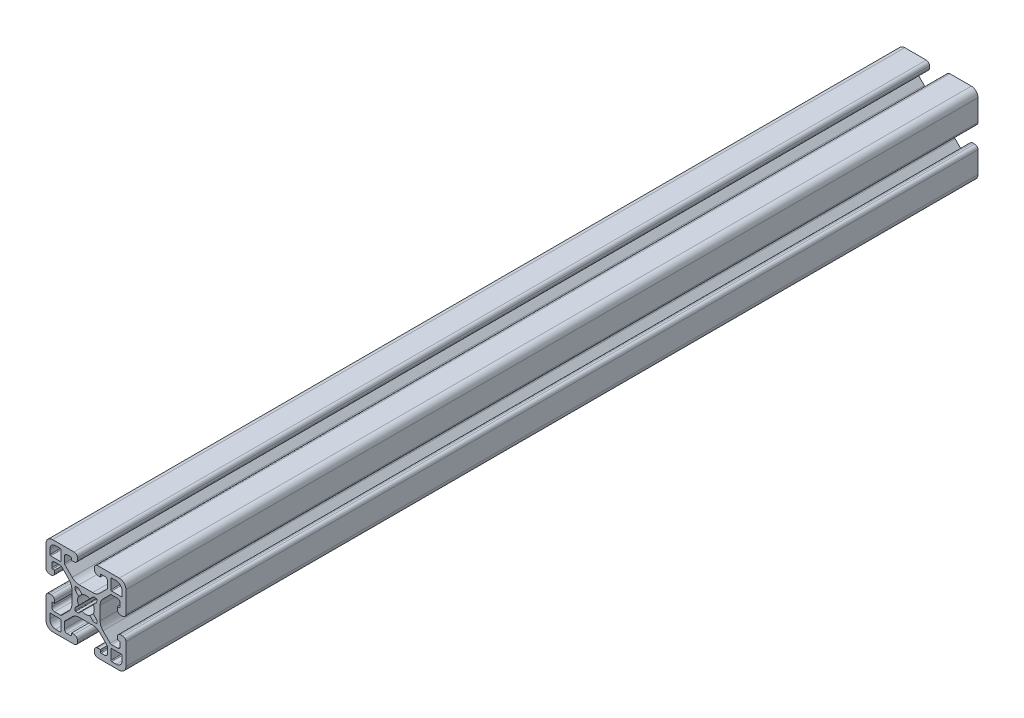
SolidWorks part; units mm, degrees
material "6105-T5 Aluminum"
ref_plane "Front Plane" through (0, 0, 0) normal (0, 0, 1) x (1, 0, 0)
ref_plane "Top Plane" through (0, 0, 0) normal (0, 1, 0) x (1, 0, 0)
ref_plane "Right Plane" through (0, 0, 0) normal (1, 0, 0) x (0, 0, -1)
sketch "Sketch1" plane through (0, 0, 0) normal (0, 0, 1) x (1, 0, 0)
  line L0 (-12.2428, -17.2466) -> (-14.4526, -17.2466)
  line L1 (-17.2466, -14.4526) -> (-17.2466, -12.2428)
  line L2 (-16.8656, -11.8618) -> (-12.2428, -11.8618)
  line L3 (-11.8618, -12.2428) -> (-11.8618, -16.8656)
  line L4 (12.2428, 17.2466) -> (14.4526, 17.2466)
  line L5 (17.2466, 14.4526) -> (17.2466, 12.2428)
  line L6 (16.8656, 11.8618) -> (12.2428, 11.8618)
  line L7 (11.8618, 12.2428) -> (11.8618, 16.8656)
  line L8 (1.5823, 3.1988) -> (3.3048, 4.9212)
  line L9 (3.9334, 5.1816) -> (4.9276, 5.1816)
  line L10 (5.1816, 4.9276) -> (5.1816, 3.9334)
  line L11 (4.9212, 3.3048) -> (3.1988, 1.5823)
  line L12 (3.1988, -1.5823) -> (4.9212, -3.3048)
  line L13 (5.1816, -3.9334) -> (5.1816, -4.9276)
  line L14 (4.9276, -5.1816) -> (3.9334, -5.1816)
  line L15 (3.3048, -4.9212) -> (1.5823, -3.1988)
  line L16 (-1.5823, -3.1988) -> (-3.3048, -4.9212)
  line L17 (-3.9334, -5.1816) -> (-4.9276, -5.1816)
  line L18 (-5.1816, -4.9276) -> (-5.1816, -3.9334)
  line L19 (-4.9212, -3.3048) -> (-3.1988, -1.5823)
  line L20 (-3.1988, 1.5823) -> (-4.9212, 3.3048)
  line L21 (-5.1816, 3.9334) -> (-5.1816, 4.9276)
  line L22 (-4.9276, 5.1816) -> (-3.9334, 5.1816)
  line L23 (-3.3048, 4.9212) -> (-1.5823, 3.1988)
  line L24 (-17.2466, 12.2428) -> (-17.2466, 14.4526)
  line L25 (-14.4526, 17.2466) -> (-12.2428, 17.2466)
  line L26 (-11.8618, 16.8656) -> (-11.8618, 12.2428)
  line L27 (-12.2428, 11.8618) -> (-16.8656, 11.8618)
  line L28 (17.2466, -12.2428) -> (17.2466, -14.4526)
  line L29 (14.4526, -17.2466) -> (12.2428, -17.2466)
  line L30 (11.8618, -16.8656) -> (11.8618, -12.2428)
  line L31 (12.2428, -11.8618) -> (16.8656, -11.8618)
  line L32 (-16.2859, 7.239) -> (-16.2859, 9.017)
  line L33 (-15.0159, 10.287) -> (-12.2178, 10.287)
  line L34 (-11.5892, 10.0266) -> (-8.1292, 6.5666)
  line L35 (-6.738, 3.208) -> (-6.738, -3.208)
  line L36 (-8.1292, -6.5666) -> (-11.5892, -10.0266)
  line L37 (-12.2178, -10.287) -> (-15.0159, -10.287)
  line L38 (-16.2859, -9.017) -> (-16.2859, -7.239)
  line L39 (-15.9049, -6.858) -> (-14.986, -6.858)
  line L40 (-14.986, -6.858) -> (-14.986, -5.6388)
  line L41 (-16.5608, -4.064) -> (-17.4752, -4.064)
  line L42 (-19.05, -5.6388) -> (-19.05, -15.875)
  line L43 (-15.875, -19.05) -> (-5.6388, -19.05)
  line L44 (-4.064, -17.4752) -> (-4.064, -16.5608)
  line L45 (-5.6388, -14.986) -> (-6.858, -14.986)
  line L46 (-6.858, -14.986) -> (-6.858, -15.9049)
  line L47 (-7.239, -16.2859) -> (-9.017, -16.2859)
  line L48 (-10.287, -15.0159) -> (-10.287, -12.2178)
  line L49 (-10.0266, -11.5892) -> (-6.5666, -8.1292)
  line L50 (-3.208, -6.738) -> (3.208, -6.738)
  line L51 (6.5666, -8.1292) -> (10.0266, -11.5892)
  line L52 (10.287, -12.2178) -> (10.287, -15.0159)
  line L53 (9.017, -16.2859) -> (7.239, -16.2859)
  line L54 (6.858, -15.9049) -> (6.858, -14.986)
  line L55 (6.858, -14.986) -> (5.6388, -14.986)
  line L56 (4.064, -16.5608) -> (4.064, -17.4752)
  line L57 (5.6388, -19.05) -> (15.875, -19.05)
  line L58 (19.05, -15.875) -> (19.05, -5.6388)
  line L59 (17.4752, -4.064) -> (16.5608, -4.064)
  line L60 (14.986, -5.6388) -> (14.986, -6.858)
  line L61 (14.986, -6.858) -> (15.9049, -6.858)
  line L62 (16.2859, -7.239) -> (16.2859, -9.017)
  line L63 (15.0159, -10.287) -> (12.2178, -10.287)
  line L64 (11.5892, -10.0266) -> (8.1292, -6.5666)
  line L65 (6.738, -3.208) -> (6.738, 3.208)
  line L66 (8.1292, 6.5666) -> (11.5892, 10.0266)
  line L67 (12.2178, 10.287) -> (15.0159, 10.287)
  line L68 (16.2859, 9.017) -> (16.2859, 7.239)
  line L69 (15.9049, 6.858) -> (14.986, 6.858)
  line L70 (14.986, 6.858) -> (14.986, 5.6388)
  line L71 (16.5608, 4.064) -> (17.4752, 4.064)
  line L72 (19.05, 5.6388) -> (19.05, 15.875)
  line L73 (15.875, 19.05) -> (5.6388, 19.05)
  line L74 (4.064, 17.4752) -> (4.064, 16.5608)
  line L75 (5.6388, 14.986) -> (6.858, 14.986)
  line L76 (6.858, 14.986) -> (6.858, 15.9049)
  line L77 (7.239, 16.2859) -> (9.017, 16.2859)
  line L78 (10.287, 15.0159) -> (10.287, 12.2178)
  line L79 (10.0266, 11.5892) -> (6.5666, 8.1292)
  line L80 (3.208, 6.738) -> (-3.208, 6.738)
  line L81 (-6.5666, 8.1292) -> (-10.0266, 11.5892)
  line L82 (-10.287, 12.2178) -> (-10.287, 15.0159)
  line L83 (-9.017, 16.2859) -> (-7.239, 16.2859)
  line L84 (-6.858, 15.9049) -> (-6.858, 14.986)
  line L85 (-6.858, 14.986) -> (-5.6388, 14.986)
  line L86 (-4.064, 16.5608) -> (-4.064, 17.4752)
  line L87 (-5.6388, 19.05) -> (-15.875, 19.05)
  line L88 (-19.05, 15.875) -> (-19.05, 5.6388)
  line L89 (-17.4752, 4.064) -> (-16.5608, 4.064)
  line L90 (-14.986, 5.6388) -> (-14.986, 6.858)
  line L91 (-14.986, 6.858) -> (-15.9049, 6.858)
  arc A0 (-17.2466, -14.4526) -> (-14.4526, -17.2466) centre (-14.4526, -14.4526) ccw
  arc A1 (-16.8656, -11.8618) -> (-17.2466, -12.2428) centre (-16.8656, -12.2428) ccw
  arc A2 (-11.8618, -12.2428) -> (-12.2428, -11.8618) centre (-12.2428, -12.2428) ccw
  arc A3 (-12.2428, -17.2466) -> (-11.8618, -16.8656) centre (-12.2428, -16.8656) ccw
  arc A4 (17.2466, 14.4526) -> (14.4526, 17.2466) centre (14.4526, 14.4526) ccw
  arc A5 (16.8656, 11.8618) -> (17.2466, 12.2428) centre (16.8656, 12.2428) ccw
  arc A6 (11.8618, 12.2428) -> (12.2428, 11.8618) centre (12.2428, 12.2428) ccw
  arc A7 (12.2428, 17.2466) -> (11.8618, 16.8656) centre (12.2428, 16.8656) ccw
  arc A8 (1.178, 3.1119) -> (-1.178, 3.1119) centre (0, 0) ccw
  arc A9 (1.178, 3.1119) -> (1.5823, 3.1988) centre (1.3129, 3.4682) ccw
  arc A10 (3.9334, 5.1816) -> (3.3048, 4.9212) centre (3.9334, 4.2926) ccw
  arc A11 (5.1816, 4.9276) -> (4.9276, 5.1816) centre (4.9276, 4.9276) ccw
  arc A12 (4.9212, 3.3048) -> (5.1816, 3.9334) centre (4.2926, 3.9334) ccw
  arc A13 (3.1988, 1.5823) -> (3.1119, 1.178) centre (3.4682, 1.3129) ccw
  arc A14 (3.1119, -1.178) -> (3.1119, 1.178) centre (0, 0) ccw
  arc A15 (3.1119, -1.178) -> (3.1988, -1.5823) centre (3.4682, -1.3129) ccw
  arc A16 (5.1816, -3.9334) -> (4.9212, -3.3048) centre (4.2926, -3.9334) ccw
  arc A17 (4.9276, -5.1816) -> (5.1816, -4.9276) centre (4.9276, -4.9276) ccw
  arc A18 (3.3048, -4.9212) -> (3.9334, -5.1816) centre (3.9334, -4.2926) ccw
  arc A19 (1.5823, -3.1988) -> (1.178, -3.1119) centre (1.3129, -3.4682) ccw
  arc A20 (-1.178, -3.1119) -> (1.178, -3.1119) centre (0, 0) ccw
  arc A21 (-1.178, -3.1119) -> (-1.5823, -3.1988) centre (-1.3129, -3.4682) ccw
  arc A22 (-3.9334, -5.1816) -> (-3.3048, -4.9212) centre (-3.9334, -4.2926) ccw
  arc A23 (-5.1816, -4.9276) -> (-4.9276, -5.1816) centre (-4.9276, -4.9276) ccw
  arc A24 (-4.9212, -3.3048) -> (-5.1816, -3.9334) centre (-4.2926, -3.9334) ccw
  arc A25 (-3.1988, -1.5823) -> (-3.1119, -1.178) centre (-3.4682, -1.3129) ccw
  arc A26 (-3.1119, 1.178) -> (-3.1119, -1.178) centre (0, 0) ccw
  arc A27 (-3.1119, 1.178) -> (-3.1988, 1.5823) centre (-3.4682, 1.3129) ccw
  arc A28 (-5.1816, 3.9334) -> (-4.9212, 3.3048) centre (-4.2926, 3.9334) ccw
  arc A29 (-4.9276, 5.1816) -> (-5.1816, 4.9276) centre (-4.9276, 4.9276) ccw
  arc A30 (-3.3048, 4.9212) -> (-3.9334, 5.1816) centre (-3.9334, 4.2926) ccw
  arc A31 (-1.5823, 3.1988) -> (-1.178, 3.1119) centre (-1.3129, 3.4682) ccw
  arc A32 (-14.4526, 17.2466) -> (-17.2466, 14.4526) centre (-14.4526, 14.4526) ccw
  arc A33 (-11.8618, 16.8656) -> (-12.2428, 17.2466) centre (-12.2428, 16.8656) ccw
  arc A34 (-12.2428, 11.8618) -> (-11.8618, 12.2428) centre (-12.2428, 12.2428) ccw
  arc A35 (-17.2466, 12.2428) -> (-16.8656, 11.8618) centre (-16.8656, 12.2428) ccw
  arc A36 (14.4526, -17.2466) -> (17.2466, -14.4526) centre (14.4526, -14.4526) ccw
  arc A37 (11.8618, -16.8656) -> (12.2428, -17.2466) centre (12.2428, -16.8656) ccw
  arc A38 (12.2428, -11.8618) -> (11.8618, -12.2428) centre (12.2428, -12.2428) ccw
  arc A39 (17.2466, -12.2428) -> (16.8656, -11.8618) centre (16.8656, -12.2428) ccw
  arc A40 (-16.2859, 7.239) -> (-15.9049, 6.858) centre (-15.9049, 7.239) ccw
  arc A41 (-15.0159, 10.287) -> (-16.2859, 9.017) centre (-15.0159, 9.017) ccw
  arc A42 (-11.5892, 10.0266) -> (-12.2178, 10.287) centre (-12.2178, 9.398) ccw
  arc A43 (-6.738, 3.208) -> (-8.1292, 6.5666) centre (-11.4878, 3.208) ccw
  arc A44 (-8.1292, -6.5666) -> (-6.738, -3.208) centre (-11.4878, -3.208) ccw
  arc A45 (-12.2178, -10.287) -> (-11.5892, -10.0266) centre (-12.2178, -9.398) ccw
  arc A46 (-16.2859, -9.017) -> (-15.0159, -10.287) centre (-15.0159, -9.017) ccw
  arc A47 (-15.9049, -6.858) -> (-16.2859, -7.239) centre (-15.9049, -7.239) ccw
  arc A48 (-14.986, -5.6388) -> (-16.5608, -4.064) centre (-16.5608, -5.6388) ccw
  arc A49 (-17.4752, -4.064) -> (-19.05, -5.6388) centre (-17.4752, -5.6388) ccw
  arc A50 (-19.05, -15.875) -> (-15.875, -19.05) centre (-15.875, -15.875) ccw
  arc A51 (-5.6388, -19.05) -> (-4.064, -17.4752) centre (-5.6388, -17.4752) ccw
  arc A52 (-4.064, -16.5608) -> (-5.6388, -14.986) centre (-5.6388, -16.5608) ccw
  arc A53 (-7.239, -16.2859) -> (-6.858, -15.9049) centre (-7.239, -15.9049) ccw
  arc A54 (-10.287, -15.0159) -> (-9.017, -16.2859) centre (-9.017, -15.0159) ccw
  arc A55 (-10.0266, -11.5892) -> (-10.287, -12.2178) centre (-9.398, -12.2178) ccw
  arc A56 (-3.208, -6.738) -> (-6.5666, -8.1292) centre (-3.208, -11.4878) ccw
  arc A57 (6.5666, -8.1292) -> (3.208, -6.738) centre (3.208, -11.4878) ccw
  arc A58 (10.287, -12.2178) -> (10.0266, -11.5892) centre (9.398, -12.2178) ccw
  arc A59 (9.017, -16.2859) -> (10.287, -15.0159) centre (9.017, -15.0159) ccw
  arc A60 (6.858, -15.9049) -> (7.239, -16.2859) centre (7.239, -15.9049) ccw
  arc A61 (5.6388, -14.986) -> (4.064, -16.5608) centre (5.6388, -16.5608) ccw
  arc A62 (4.064, -17.4752) -> (5.6388, -19.05) centre (5.6388, -17.4752) ccw
  arc A63 (15.875, -19.05) -> (19.05, -15.875) centre (15.875, -15.875) ccw
  arc A64 (19.05, -5.6388) -> (17.4752, -4.064) centre (17.4752, -5.6388) ccw
  arc A65 (16.5608, -4.064) -> (14.986, -5.6388) centre (16.5608, -5.6388) ccw
  arc A66 (16.2859, -7.239) -> (15.9049, -6.858) centre (15.9049, -7.239) ccw
  arc A67 (15.0159, -10.287) -> (16.2859, -9.017) centre (15.0159, -9.017) ccw
  arc A68 (11.5892, -10.0266) -> (12.2178, -10.287) centre (12.2178, -9.398) ccw
  arc A69 (6.738, -3.208) -> (8.1292, -6.5666) centre (11.4878, -3.208) ccw
  arc A70 (8.1292, 6.5666) -> (6.738, 3.208) centre (11.4878, 3.208) ccw
  arc A71 (12.2178, 10.287) -> (11.5892, 10.0266) centre (12.2178, 9.398) ccw
  arc A72 (16.2859, 9.017) -> (15.0159, 10.287) centre (15.0159, 9.017) ccw
  arc A73 (15.9049, 6.858) -> (16.2859, 7.239) centre (15.9049, 7.239) ccw
  arc A74 (14.986, 5.6388) -> (16.5608, 4.064) centre (16.5608, 5.6388) ccw
  arc A75 (17.4752, 4.064) -> (19.05, 5.6388) centre (17.4752, 5.6388) ccw
  arc A76 (19.05, 15.875) -> (15.875, 19.05) centre (15.875, 15.875) ccw
  arc A77 (5.6388, 19.05) -> (4.064, 17.4752) centre (5.6388, 17.4752) ccw
  arc A78 (4.064, 16.5608) -> (5.6388, 14.986) centre (5.6388, 16.5608) ccw
  arc A79 (7.239, 16.2859) -> (6.858, 15.9049) centre (7.239, 15.9049) ccw
  arc A80 (10.287, 15.0159) -> (9.017, 16.2859) centre (9.017, 15.0159) ccw
  arc A81 (10.0266, 11.5892) -> (10.287, 12.2178) centre (9.398, 12.2178) ccw
  arc A82 (3.208, 6.738) -> (6.5666, 8.1292) centre (3.208, 11.4878) ccw
  arc A83 (-6.5666, 8.1292) -> (-3.208, 6.738) centre (-3.208, 11.4878) ccw
  arc A84 (-10.287, 12.2178) -> (-10.0266, 11.5892) centre (-9.398, 12.2178) ccw
  arc A85 (-9.017, 16.2859) -> (-10.287, 15.0159) centre (-9.017, 15.0159) ccw
  arc A86 (-6.858, 15.9049) -> (-7.239, 16.2859) centre (-7.239, 15.9049) ccw
  arc A87 (-5.6388, 14.986) -> (-4.064, 16.5608) centre (-5.6388, 16.5608) ccw
  arc A88 (-4.064, 17.4752) -> (-5.6388, 19.05) centre (-5.6388, 17.4752) ccw
  arc A89 (-15.875, 19.05) -> (-19.05, 15.875) centre (-15.875, 15.875) ccw
  arc A90 (-19.05, 5.6388) -> (-17.4752, 4.064) centre (-17.4752, 5.6388) ccw
  arc A91 (-16.5608, 4.064) -> (-14.986, 5.6388) centre (-16.5608, 5.6388) ccw
extrude "Extrude1" add sketch "Sketch1" against normal blind 406.4
hole_wizard "7060-LEFT" positions "Sketch3" profile "Sketch2" tap size "5/16-18" standard "Ansi Inch"
sketch "Sketch3" plane through (0, 0, 0) normal (0, 0, 1) x (1, 0, 0)
  point P1 (0, 0)
sketch "Sketch2" plane through (0, 0, 0) normal (1, 0, 0) x (0, -1, 0)
  line L0 (0, 0) -> (0, 22.1161)
  line L1 (0, 22.1161) -> (3.3274, 20.1168)
  line L2 (3.3274, 20.1168) -> (3.3274, 0)
  line L5 (3.3274, 0) -> (0, 0)
  line L10 (0, 22.1161) -> (-3.3274, 20.1168) construction
  line L11 (0, -6.35) -> (0, 107.95) construction
  dimension "Tap Drill Dia." = 6.6548
  dimension "Tap Drill Depth" = 20.1168
  dimension "Drill Angle" = 118
hole_wizard "7060-RIGHT" positions "Sketch5" profile "Sketch4" tap size "5/16-18" standard "Ansi Inch"
sketch "Sketch5" plane through (0, 0, -406.4) normal (0, 0, -1) x (-1, 0, 0)
  point P1 (0, 0)
sketch "Sketch4" plane through (0, 0, -406.4) normal (1, 0, 0) x (0, 1, 0)
  line L0 (0, 0) -> (0, 22.1161)
  line L1 (0, 22.1161) -> (3.3274, 20.1168)
  line L2 (3.3274, 20.1168) -> (3.3274, 0)
  line L5 (3.3274, 0) -> (0, 0)
  line L10 (0, 22.1161) -> (-3.3274, 20.1168) construction
  line L11 (0, -6.35) -> (0, 107.95) construction
  dimension "Tap Drill Dia." = 6.6548
  dimension "Tap Drill Depth" = 20.1168
  dimension "Drill Angle" = 118
hole_wizard "7025-LEFT" positions "Sketch7" profile "Sketch6" tap size "3/8-16" standard "Ansi Inch"
sketch "Sketch7" plane through (0, 0, 0) normal (0, 0, 1) x (1, 0, 0)
  point P1 (0, 0)
sketch "Sketch6" plane through (0, 0, 0) normal (1, 0, 0) x (0, -1, 0)
  line L0 (0, 0) -> (0, 26.2099)
  line L1 (0, 26.2099) -> (3.9687, 23.8252)
  line L2 (3.9687, 23.8252) -> (3.9687, 0)
  line L5 (3.9687, 0) -> (0, 0)
  line L10 (0, 26.2099) -> (-3.9688, 23.8252) construction
  line L11 (0, -6.35) -> (0, 107.95) construction
  dimension "Tap Drill Dia." = 7.9375
  dimension "Tap Drill Depth" = 23.8252
  dimension "Drill Angle" = 118
cosmetic thread "Hole Thread1" parameters "D1"=19.05, "D2"=9.525
sketch "Sketch8" plane through (0, 19.05, 0) normal (0, 1, 0) x (-1, 0, 0)
  line L0 (5.6388, 0) -> (15.875, 0) construction
  circle A0 centre (0, -171.45) radius 3.7465
  dimension "D1" = 7.493
  dimension "D2" = 171.45
extrude "7050-R-OPEN" cut sketch "Sketch8" against normal through all
sketch "Sketch9" plane through (19.05, 0, 0) normal (1, 0, 0) x (0, 0, -1)
  line L0 (0, 5.6388) -> (0, 15.875) construction
  circle A0 centre (273.05, 0) radius 3.7465
  dimension "D1" = 7.493
  dimension "D2" = 273.05
extrude "7050-S-OPEN" cut sketch "Sketch9" against normal through all
